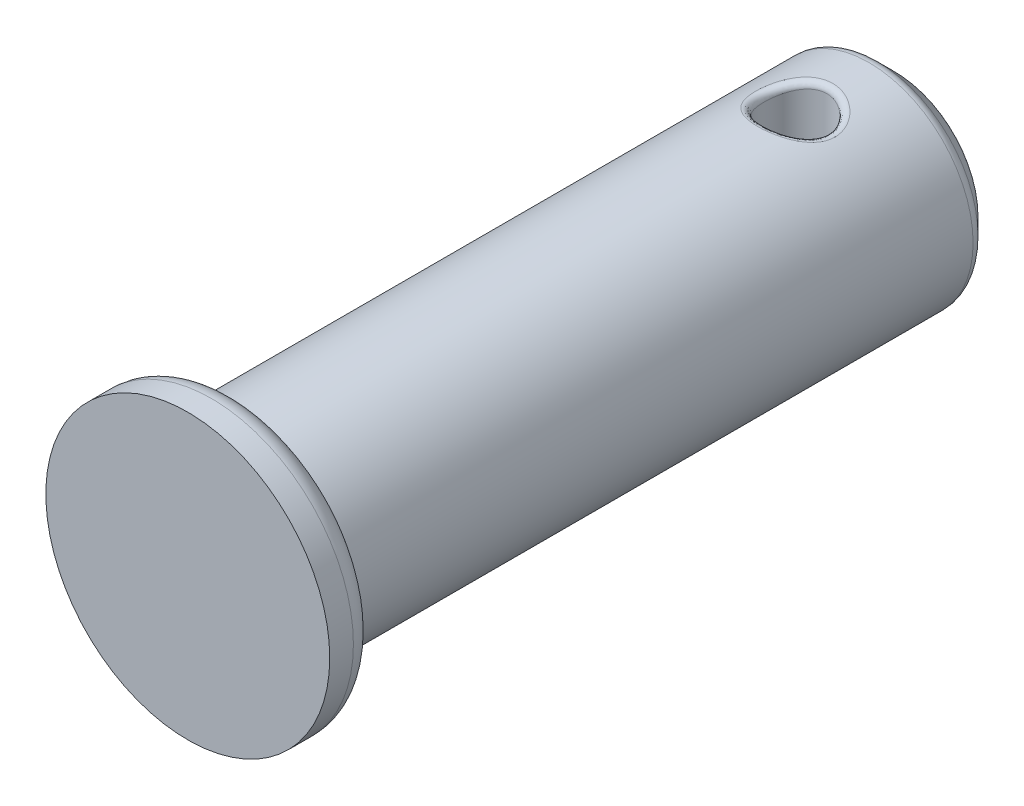
SolidWorks part; units mm, degrees
ref_plane "Front Plane" through (0, 0, 0) normal (0, 0, 1) x (1, 0, 0)
ref_plane "Top Plane" through (0, 0, 0) normal (0, 1, 0) x (1, 0, 0)
ref_plane "Right Plane" through (0, 0, 0) normal (1, 0, 0) x (0, 0, -1)
sketch "Sketch1" plane through (0, 0, 0) normal (0, 0, 1) x (1, 0, 0)
  circle A0 centre (0, 0) radius 3.4925
  dimension "D1" = 6.985
extrude "Boss-Extrude1" add sketch "Sketch1" along normal blind 22.225
sketch "Sketch2" plane through (0, 0, 22.225) normal (0, 0, 1) x (1, 0, 0)
  circle A2 centre (0, 0) radius 4.7625
  circle A3 centre (0, 0) radius 4.7625
  dimension "D1" = 1.27
extrude "Boss-Extrude2" add sketch "Sketch2" along normal blind 1.5875
sketch "Sketch3" plane through (0, 0, 0) normal (0, 1, 0) x (1, 0, 0)
  circle A0 centre (0, -3.429) radius 1.0583
  dimension "D1" = 2.1167
  dimension "D2" = 3.429
extrude "Cut-Extrude1" cut sketch "Sketch3" against normal through all both and the other way through all
fillet "Fillet1" radius 0.1984 2 edges at (-0.1905, -3.4873, 2.388) (0.1905, 3.4873, 2.388)
fillet "Fillet3" radius 0.7937 1 edges at (4.7625, 0, 22.225)
chamfer "Chamfer1" distance 0.7937 angle 45 1 edges at (3.4925, 0, 0)
fillet "Fillet4" radius 0.3969 2 edges at (2.6987, 0, 0) (3.4925, 0, 0.7938)
